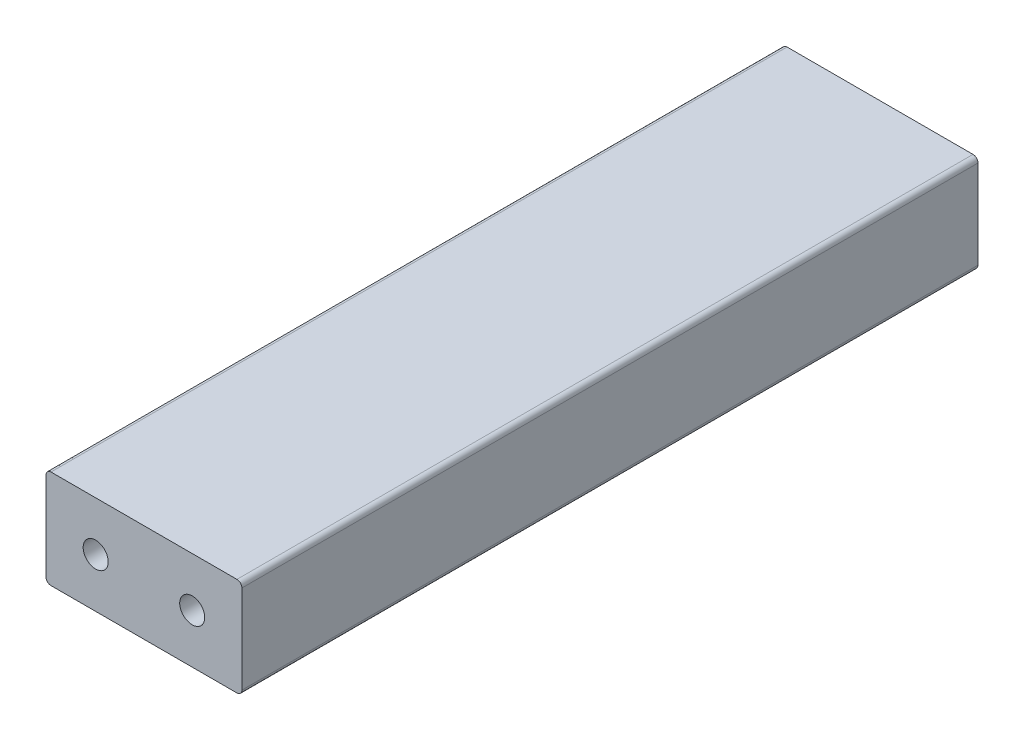
SolidWorks part; units mm, degrees
ref_plane "Front Plane" through (0, 0, 0) normal (0, 0, 1) x (1, 0, 0)
ref_plane "Top Plane" through (0, 0, 0) normal (0, 1, 0) x (1, 0, 0)
ref_plane "Right Plane" through (0, 0, 0) normal (1, 0, 0) x (0, 0, -1)
sketch "Sketch1" plane through (0, 0, 0) normal (0, 0, 1) x (1, 0, 0)
  line L1 (-19.9771, 10.033) -> (19.9771, 10.033)
  line L2 (-19.9771, 10.033) -> (-19.9771, -10.033)
  line L3 (-19.9771, -10.033) -> (19.9771, -10.033)
  line L4 (19.9771, 10.033) -> (19.9771, -10.033)
  line L5 (-19.9771, 10.033) -> (19.9771, -10.033) construction
  line L6 (-19.9771, -10.033) -> (19.9771, 10.033) construction
  point P0 (0, 0)
  dimension "D1" = 39.9542
  dimension "D2" = 20.066
extrude "Boss-Extrude1" add sketch "Sketch1" along normal mid plane 150.114
fillet "Fillet1" radius 1.016 4 edges at (19.9771, -10.033, 0) (19.9771, 10.033, 0) (-19.9771, -10.033, 0) (-19.9771, 10.033, 0)
hole_wizard "1/4-20 Tapped Hole1" positions "Sketch2" profile "Sketch4" tap size "1/4-20" standard "ANSI Inch"
sketch "Sketch2" plane through (0, 0, -75.057) normal (0, 0, -1) x (-1, 0, 0)
  point P0 (-9.8425, 0)
  point P2 (9.8425, 0)
  dimension "D1" = 9.8425
  dimension "D2" = 19.685
cosmetic thread "Hole Thread1"
cosmetic thread "Hole Thread2"
sketch "Sketch4" plane through (9.8425, 0, -75.057) normal (1, 0, 0) x (0, 1, 0)
  line L0 (0, 0) -> (0, 18.0438)
  line L1 (0, 18.0438) -> (2.5527, 16.51)
  line L2 (2.5527, 16.51) -> (2.5527, 0)
  line L5 (2.5527, 0) -> (0, 0)
  line L10 (0, 18.0438) -> (-2.5527, 16.51) construction
  line L11 (0, -6.35) -> (0, 107.95) construction
  dimension "Tap Drill Dia." = 5.1054
  dimension "Tap Drill Depth" = 16.51
  dimension "Drill Angle" = 118
mirror "Mirror1" about plane through (0, 0, 0) normal (0, 0, 1) of "1/4-20 Tapped Hole1"
